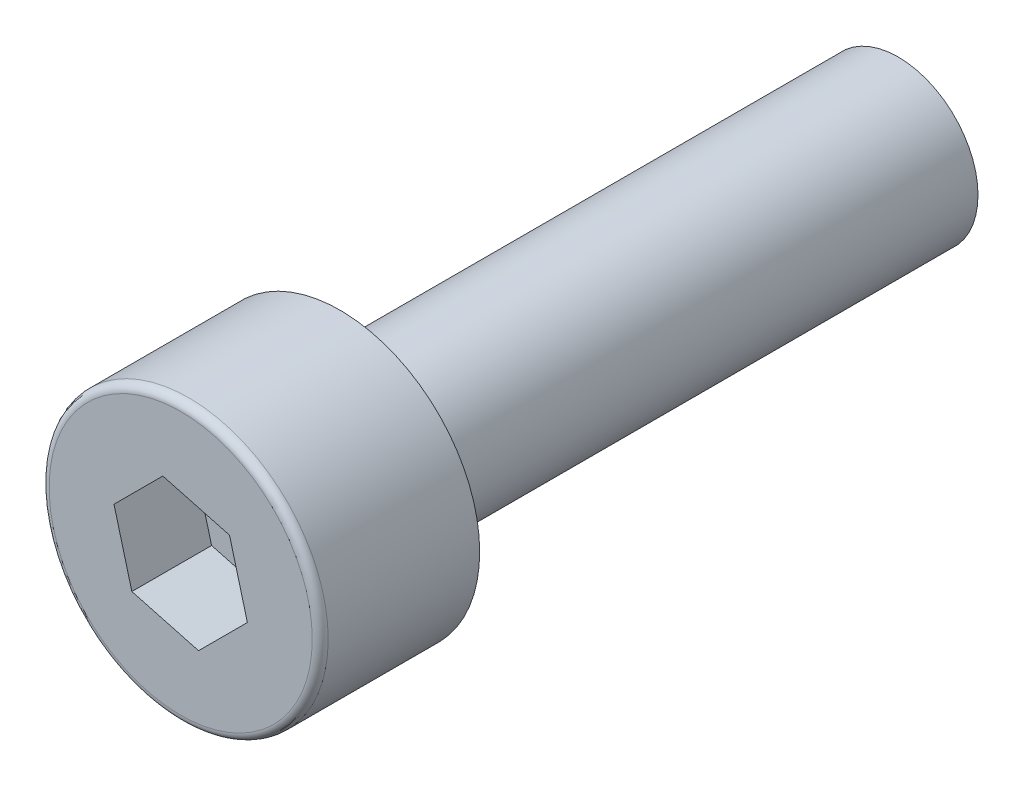
SolidWorks part; units mm, degrees
ref_plane "前视基准面" through (0, 0, 0) normal (0, 0, 1) x (1, 0, 0)
ref_plane "上视基准面" through (0, 0, 0) normal (0, 1, 0) x (1, 0, 0)
ref_plane "右视基准面" through (0, 0, 0) normal (1, 0, 0) x (0, 0, -1)
sketch "草图1" plane through (0, 0, 0) normal (0, 0, 1) x (1, 0, 0)
  circle A0 centre (0, 0) radius 3.5
  dimension "D1" = 7
extrude "凸台-拉伸1" add sketch "草图1" along normal blind 4
sketch "草图2" plane through (0, 0, 4) normal (0, 0, 1) x (1, 0, 0)
  line L1 (-1.2247, -1.2247) -> (0.4483, -1.673)
  line L2 (0.4483, -1.673) -> (1.673, -0.4483)
  line L3 (1.673, -0.4483) -> (1.2247, 1.2247)
  line L4 (1.2247, 1.2247) -> (-0.4483, 1.673)
  line L5 (-0.4483, 1.673) -> (-1.673, 0.4483)
  line L6 (-1.673, 0.4483) -> (-1.2247, -1.2247)
  circle A0 centre (0, 0) radius 1.5 construction
  dimension "D1" = 3
extrude "切除-拉伸1" cut sketch "草图2" against normal blind 2
sketch "草图3" plane through (0, 0, 0) normal (0, 0, -1) x (-1, 0, 0)
  circle A0 centre (0, 0) radius 2
  dimension "D1" = 4
extrude "凸台-拉伸2" add sketch "草图3" along normal blind 14
fillet "圆角1" radius 0.2 1 edges at (3.5, 0, 4)
